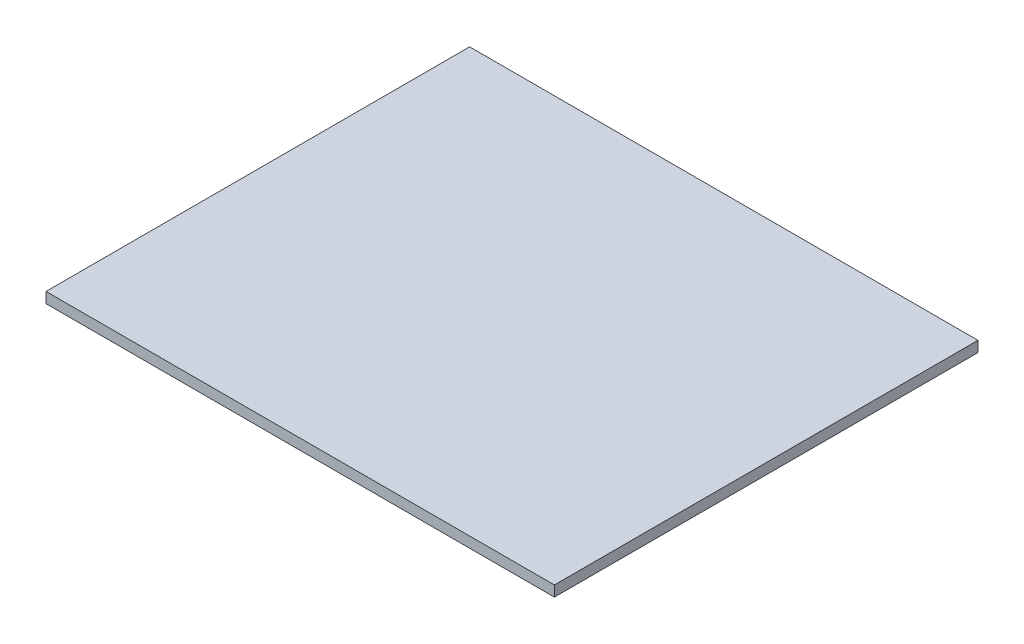
SolidWorks part; units mm, degrees
ref_plane "Front Plane" through (0, 0, 0) normal (0, 0, 1) x (1, 0, 0)
ref_plane "Top Plane" through (0, 0, 0) normal (0, 1, 0) x (1, 0, 0)
ref_plane "Right Plane" through (0, 0, 0) normal (1, 0, 0) x (0, 0, -1)
sketch "Sketch1" plane through (0, 0, 0) normal (0, 1, 0) x (1, 0, 0)
  line L1 (-152.4, -127) -> (152.4, -127)
  line L2 (-152.4, -127) -> (-152.4, 127)
  line L3 (-152.4, 127) -> (152.4, 127)
  line L4 (152.4, -127) -> (152.4, 127)
  line L5 (-152.4, -127) -> (152.4, 127) construction
  line L6 (-152.4, 127) -> (152.4, -127) construction
  point P0 (0, 0)
  dimension "D1" = 304.8
  dimension "D2" = 254
extrude "Boss-Extrude1" add sketch "Sketch1" along normal blind 6.35
